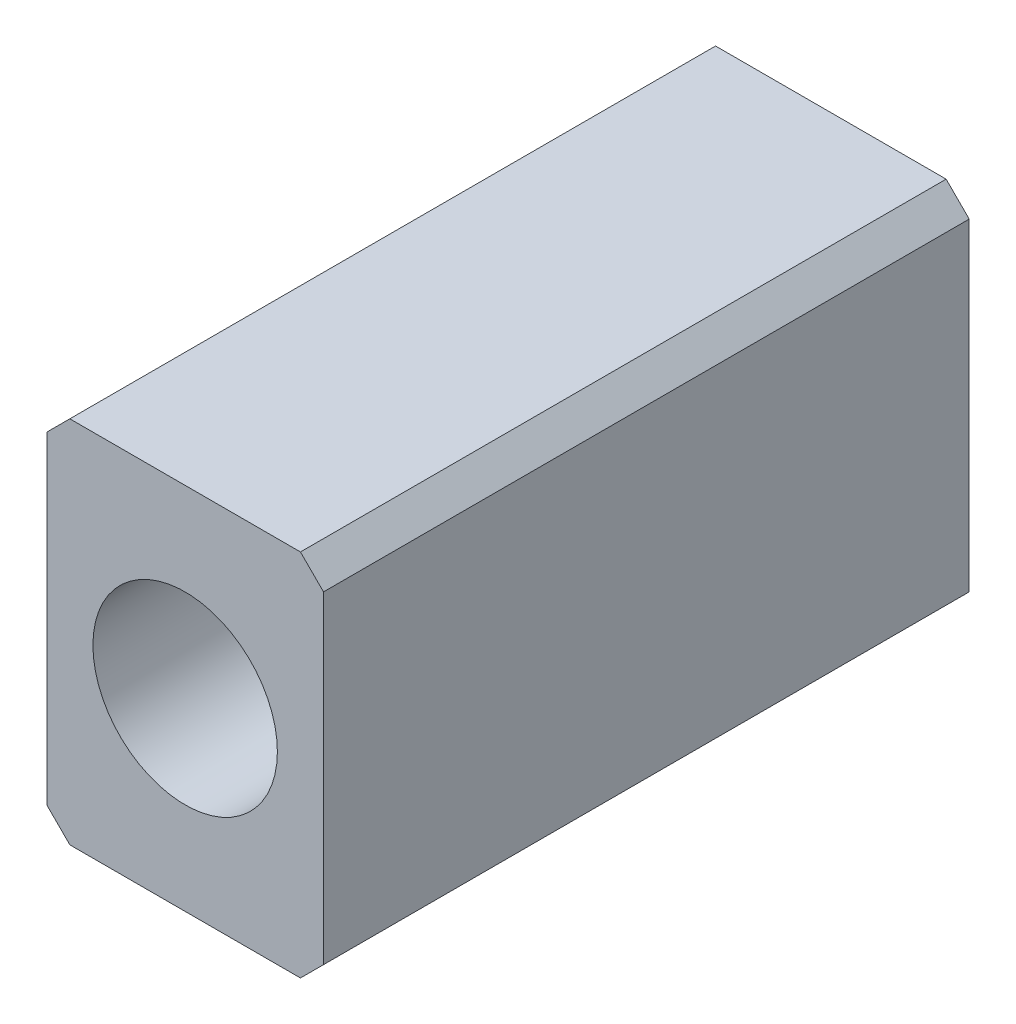
SolidWorks part; units mm, degrees
material "Alliage 2014"
ref_plane "Face" through (0, 0, 0) normal (0, 0, 1) x (1, 0, 0)
ref_plane "Dessus" through (0, 0, 0) normal (0, 1, 0) x (1, 0, 0)
ref_plane "Droite" through (0, 0, 0) normal (1, 0, 0) x (0, 0, -1)
sketch "Esquisse1" plane through (0, 0, 0) normal (0, 0, 1) x (1, 0, 0)
  line L0 (0, 8) -> (0, -8) construction
  line L1 (-6, 8) -> (6, 8)
  line L2 (-6, 8) -> (-6, -8)
  line L3 (-6, -8) -> (6, -8)
  line L4 (6, 8) -> (6, -8)
  circle A0 centre (0, 0) radius 4
  dimension "D1" = 8
  dimension "D2" = 12
  dimension "D3" = 16
extrude "Boss.-Extru.1" add sketch "Esquisse1" along normal mid plane 28
chamfer "Chanfrein1" distance 1 angle 45 4 edges at (-6, -8, 0) (6, -8, 0) (-6, 8, 0) (6, 8, 0)
hole_wizard "Trou taraudé M31" positions "Esquisse3" profile "Esquisse2" tap size "M3" standard "Iso"
sketch "Esquisse3" plane through (0, -8, 0) normal (0, -1, 0) x (-1, 0, 0)
  line L0 (0, 0) -> (17.5039, 0) construction
  line L1 (0, 14) -> (0, -14) construction
  line L2 (5, 14) -> (-5, 14) construction
  line L3 (5, -14) -> (-5, -14) construction
  point P0 (0, 8)
  point P2 (0, -8)
  dimension "D1" = 16
sketch "Esquisse2" plane through (0, -8, -8) normal (1, 0, 0) x (0, 0, -1)
  line L0 (0, 0) -> (0, 9.2511)
  line L1 (0, 9.2511) -> (1.25, 8.5)
  line L2 (1.25, 8.5) -> (1.25, 0)
  line L5 (1.25, 0) -> (0, 0)
  line L10 (0, 9.2511) -> (-1.25, 8.5) construction
  line L11 (0, -6.35) -> (0, 107.95) construction
  dimension "Diamètre du trou pour taraudage" = 2.5
  dimension "Profondeur du trou pour taraudage" = 8.5
  dimension "Angle de pointe" = 118
cosmetic thread "Filetage de perçage1" parameters "D1"=4.9147, "D2"=3
cosmetic thread "Filetage de perçage2" parameters "D1"=4.2003, "D2"=3
